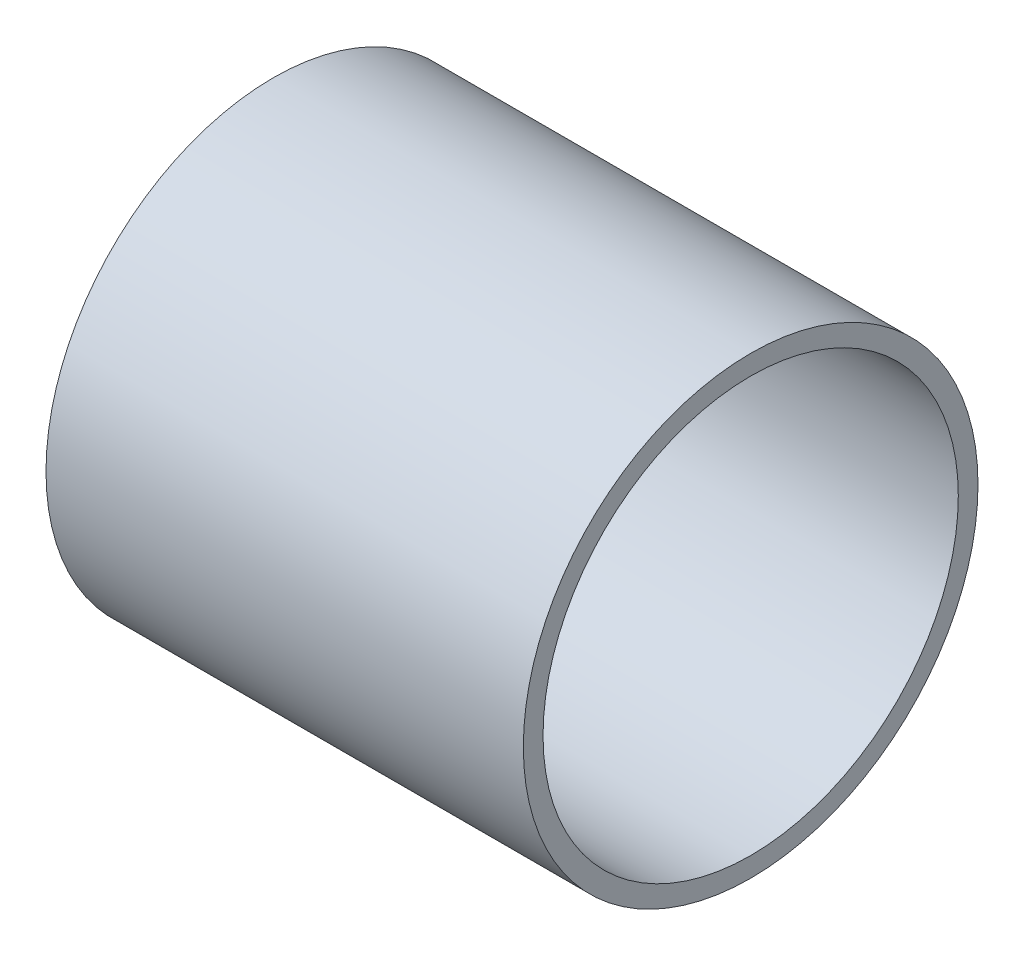
SolidWorks part; units mm, degrees
ref_plane "Alzado" through (0, 0, 0) normal (0, 0, 1) x (1, 0, 0)
ref_plane "Planta" through (0, 0, 0) normal (0, 1, 0) x (1, 0, 0)
ref_plane "Vista lateral" through (0, 0, 0) normal (1, 0, 0) x (0, 0, -1)
sketch "Croquis1" plane through (0, 0, 0) normal (1, 0, 0) x (0, 0, -1)
  circle A0 centre (0, 0) radius 19.05
  dimension "D1" = 38.1
extrude "Saliente-Extruir1" add sketch "Croquis1" along normal mid plane 40 contours A0
sketch "Croquis2" plane through (-20, 0, 0) normal (-1, 0, 0) x (0, 0, 1)
  circle A0 centre (0, 0) radius 17.4
  dimension "D1" = 34.8
extrude "Cortar-Extruir1" cut sketch "Croquis2" against normal blind 197 contours A0
